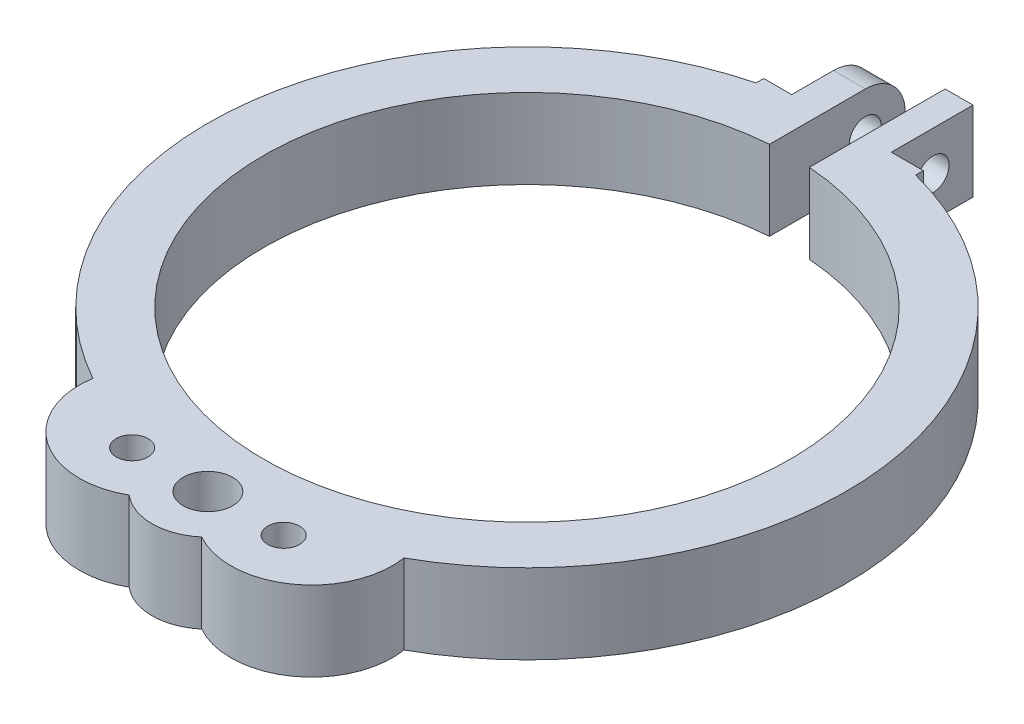
SolidWorks part; units mm, degrees
ref_plane "Alzado" through (0, 0, 0) normal (0, 0, 1) x (1, 0, 0)
ref_plane "Planta" through (0, 0, 0) normal (0, 1, 0) x (1, 0, 0)
ref_plane "Vista lateral" through (0, 0, 0) normal (1, 0, 0) x (0, 0, -1)
sketch "Croquis1" plane through (0, 0, 0) normal (0, 1, 0) x (1, 0, 0)
  line L0 (0, 0) -> (5, 0)
  line L1 (0, 0) -> (-5, 0)
  line L2 (10, 0) -> (10, 31.4484)
  line L3 (-10, 0) -> (-10, 31.4484)
  line L4 (10, 31.4484) -> (10, 38.7298)
  line L5 (-10, 31.4484) -> (-10, 38.7298)
  line L6 (5, 0) -> (5, 32.619)
  line L7 (5, 32.619) -> (5, 39.6863)
  line L8 (-5, 0) -> (-5, 32.619)
  line L9 (-5, 32.619) -> (-5, 39.6863)
  line L10 (5, 32.619) -> (10, 32.619)
  line L11 (-5, 39.6863) -> (-10, 39.6863)
  line L12 (-10, 39.6863) -> (-10, 38.7298)
  line L13 (5, 39.6863) -> (10, 39.6863)
  line L14 (10, 39.6863) -> (10, 38.7298)
  line L15 (2.5, 0) -> (2.5, 32.9052)
  line L16 (-2.5, 0) -> (-2.5, 32.9052)
  line L17 (-2.5, 32.9052) -> (-2.5, 39.9218)
  line L18 (2.5, 32.9052) -> (2.5, 39.9218)
  line L19 (2.5, 39.9218) -> (5, 39.9218)
  line L20 (5, 39.9218) -> (5, 39.6863)
  line L21 (-2.5, 39.9218) -> (-5, 39.9218)
  line L22 (-5, 39.9218) -> (-5, 39.6863)
  circle A0 centre (0, 0) radius 33
  circle A1 centre (0, 0) radius 40
extrude "Saliente-Extruir1" add sketch "Croquis1" along normal blind 10 contours L5 A1 L4 A0 | L9 A1 L5 A0 | L4 A1 L7 L10 | A1 L14 L13 | A1 L11 L12 | A0 L4 L10 | L17 A1 L9 A0 | A1 L21 L22 | L7 A1 L18 A0 | A1 L20 L19
sketch "Croquis2" plane through (0, 10, 0) normal (0, 1, 0) x (1, 0, 0)
  circle A2 centre (0, -40) radius 7
  arc A3 (-10, 38.7298) -> (10, 38.7298) centre (0, 0) ccw construction
  circle A4 centre (9.5, -36.5) radius 10.1242
  circle A5 centre (-9.5, -36.5) radius 10.1242
  arc M5 (-10, 38.7298) -> (10, 38.7298) centre (0, 0) ccw
extrude "Saliente-Extruir2" add sketch "Croquis2" against normal blind 10 contours A5 A2 M5 | A5 A2 M5 | A4 A5 A2 | A4 A2 M5 | A2 A4 M5
sketch "Croquis8" plane through (0, 10, 0) normal (0, 1, 0) x (1, 0, 0)
  circle A0 centre (9.5, -40) radius 2
  circle A1 centre (-9.5, -40) radius 2
extrude "Cortar-Extruir1" cut sketch "Croquis8" against normal blind 10
sketch "Croquis10" plane through (0, 10, 0) normal (0, 1, 0) x (1, 0, 0)
  circle A0 centre (0, -40) radius 3.1
extrude "Cortar-Extruir3" cut sketch "Croquis10" against normal blind 10
sketch "Croquis11" plane through (0, 0, -39.9218) normal (0, 0, -1) x (-1, 0, 0)
  line L1 (5, 0) -> (2.5, 0)
  line L2 (5, 0) -> (5, 10)
  line L3 (5, 10) -> (2.5, 10)
  line L4 (2.5, 0) -> (2.5, 10)
extrude "Saliente-Extruir5" add sketch "Croquis11" along normal blind 5
sketch "Croquis12" plane through (-2.5, 0, 0) normal (1, 0, 0) x (0, 0, -1)
  line L0 (44.9218, 10) -> (44.9218, 0) construction
  circle A0 centre (44.9218, 5) radius 5
  circle A1 centre (44.9218, 5) radius 2
sketch "Croquis13" plane through (-2.5, 0, 0) normal (1, 0, 0) x (0, 0, -1)
  line L0 (44.9218, 10) -> (44.9218, 0) construction
  circle A0 centre (44.9218, 5) radius 2
extrude "Cortar-Extruir4" cut sketch "Croquis13" against normal up to surface (2.5 mm away) up to face at (-5, 5, -42.304)
sketch "Croquis14" plane through (0, 0, -39.9218) normal (0, 0, -1) x (-1, 0, 0)
  line L1 (-5, 10) -> (-2.5, 10)
  line L2 (-5, 10) -> (-5, 0)
  line L3 (-5, 0) -> (-2.5, 0)
  line L4 (-2.5, 10) -> (-2.5, 0)
extrude "Saliente-Extruir7" add sketch "Croquis14" along normal blind 10
sketch "Croquis15" plane through (-2.5, 0, 0) normal (1, 0, 0) x (0, 0, -1)
  circle A0 centre (44.9218, 5) radius 2
extrude "Cortar-Extruir5" cut sketch "Croquis15" along normal blind 10
extrude "Saliente-Extruir8" add sketch "Croquis12" against normal blind 4
sketch "Croquis16" plane through (-5, 0, 0) normal (-1, 0, 0) x (0, 0, 1)
  line L0 (-44.9218, 10) -> (-39.6863, 10)
  line L1 (-39.6863, 10) -> (-39.6863, 0)
  line L2 (-39.6863, 0) -> (-44.9218, 0)
  arc A0 (-44.9218, 0) -> (-44.9218, 10) centre (-44.9218, 5) ccw
extrude "Saliente-Extruir9" add sketch "Croquis16" along normal up to surface (1.5 mm away) up to face at (-6.5, 5, -46.9218)
sketch "Croquis17" plane through (5, 0, 0) normal (1, 0, 0) x (0, 0, -1)
  line L0 (39.6863, 10) -> (49.9218, 10)
  line L1 (49.9218, 10) -> (49.9218, 0)
  line L2 (49.9218, 0) -> (39.6863, 0)
  line L3 (39.6863, 0) -> (39.6863, 10)
  circle A0 centre (44.9218, 5) radius 2
extrude "Saliente-Extruir10" add sketch "Croquis17" along normal blind 1
